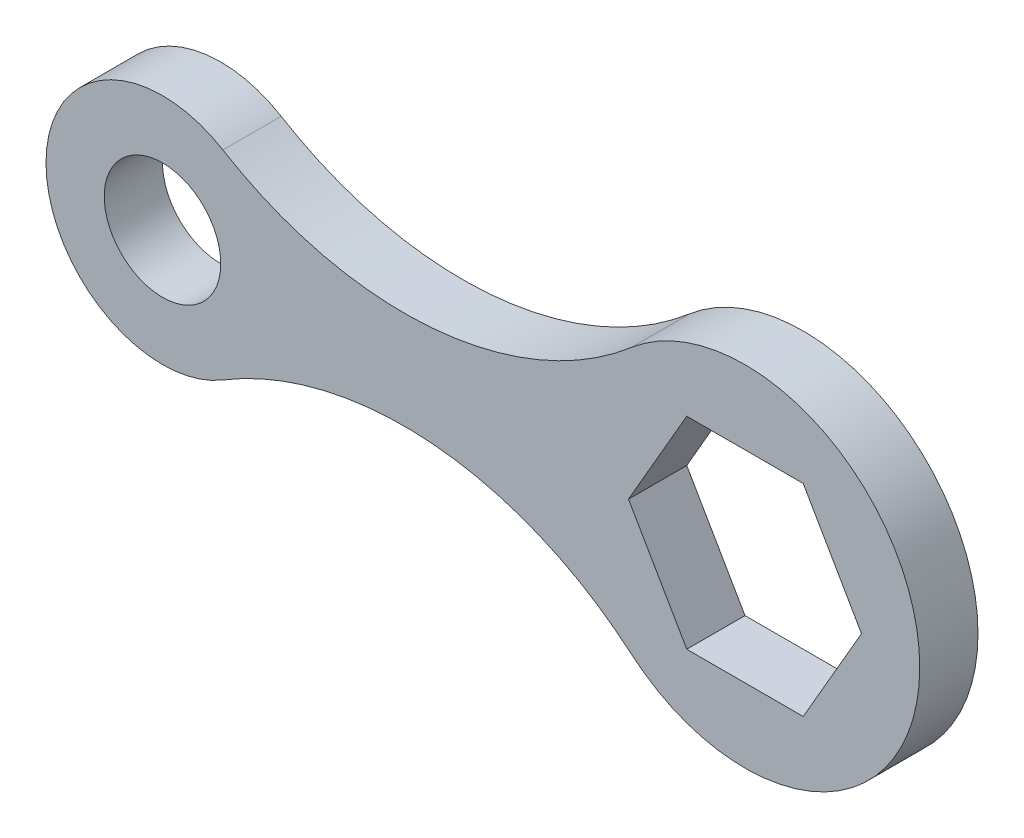
SolidWorks part; units mm, degrees
ref_plane "Front Plane" through (0, 0, 0) normal (0, 0, 1) x (1, 0, 0)
ref_plane "Top Plane" through (0, 0, 0) normal (0, 1, 0) x (1, 0, 0)
ref_plane "Right Plane" through (0, 0, 0) normal (1, 0, 0) x (0, 0, -1)
sketch "Sketch1" plane through (0, 0, 0) normal (0, 0, 1) x (1, 0, 0)
  line L0 (-100, 0) -> (-39.1941, 0) construction
  line L7 (-20, 0) -> (-10, -17.3205)
  line L8 (-10, -17.3205) -> (10, -17.3205)
  line L9 (10, -17.3205) -> (20, 0)
  line L10 (20, 0) -> (10, 17.3205)
  line L11 (10, 17.3205) -> (-10, 17.3205)
  line L12 (-10, 17.3205) -> (-20, 0)
  circle A0 centre (0, 0) radius 17.3205 construction
  arc A1 (-19.5, -22.798) -> (-19.5, 22.798) centre (0, 0) ccw
  circle A2 centre (-100, 0) radius 10
  arc A3 (-89.625, 17.0985) -> (-89.625, -17.0985) centre (-100, 0) ccw
  arc A4 (-89.625, 17.0985) -> (-19.5, 22.798) centre (-58.5, 68.3941) ccw
  arc A5 (-89.625, -17.0985) -> (-19.5, -22.798) centre (-58.5, -68.3941) cw
  point P10 (0, 17.3205)
  dimension "D2" = 60
  dimension "D3" = 20
  dimension "D4" = 40
  dimension "D5" = 100
  dimension "D6" = 60
  dimension "D1" = 20
extrude "Boss-Extrude1" add sketch "Sketch1" along normal mid plane 10
